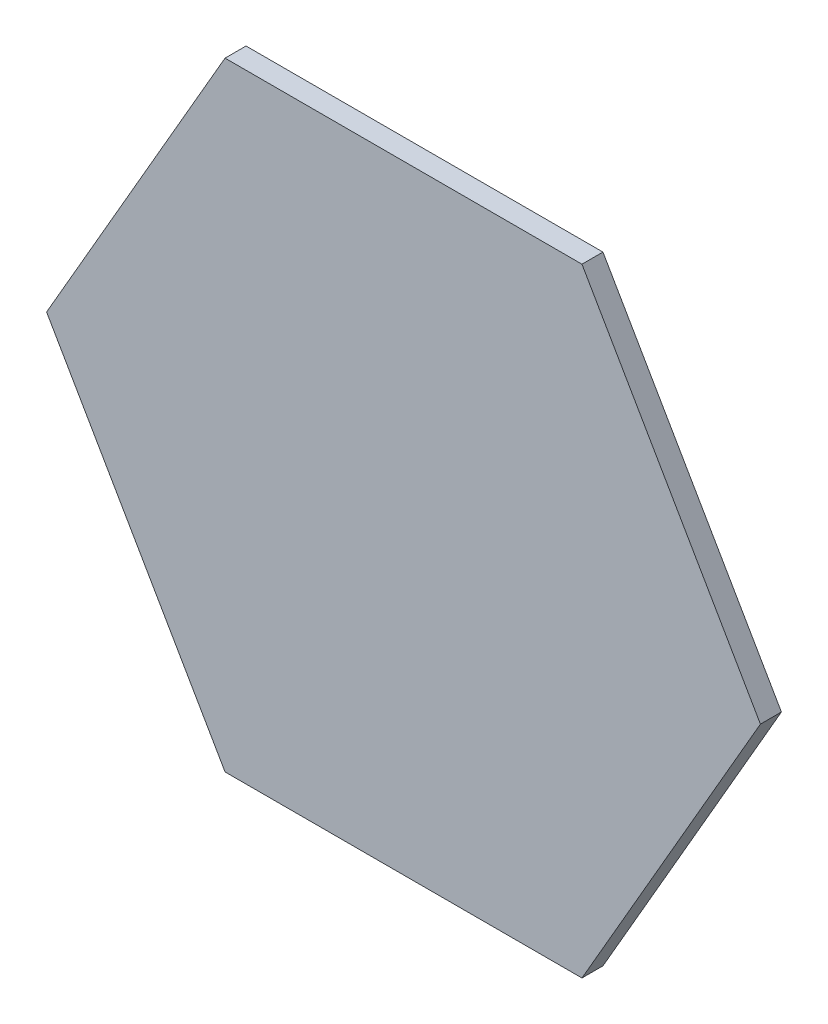
SolidWorks part; units mm, degrees
ref_plane "Front" through (0, 0, 0) normal (0, 0, 1) x (1, 0, 0)
ref_plane "Top" through (0, 0, 0) normal (0, 1, 0) x (1, 0, 0)
ref_plane "Right" through (0, 0, 0) normal (1, 0, 0) x (0, 0, -1)
sketch "Sketch1" plane through (0, 0, 0) normal (0, 0, 1) x (1, 0, 0)
  line L1 (34, 0) -> (17, 29.4449)
  line L2 (17, 29.4449) -> (-17, 29.4449)
  line L3 (-17, 29.4449) -> (-34, 0)
  line L4 (-34, 0) -> (-17, -29.4449)
  line L5 (-17, -29.4449) -> (17, -29.4449)
  line L6 (17, -29.4449) -> (34, 0)
  circle A0 centre (0, 0) radius 29.4449 construction
  dimension "D1" = 34
extrude "Boss-Extrude1" add sketch "Sketch1" along normal blind 2
